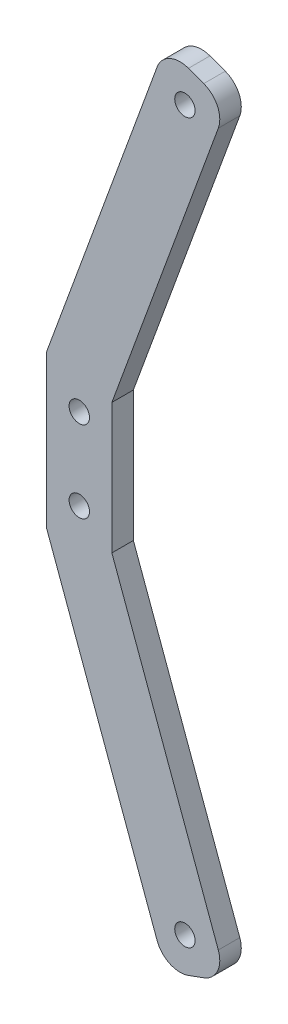
SolidWorks part; units mm, degrees
material "Titanium"
ref_plane "Front Plane" through (0, 0, 0) normal (0, 0, 1) x (1, 0, 0)
ref_plane "Top Plane" through (0, 0, 0) normal (0, 1, 0) x (1, 0, 0)
ref_plane "Right Plane" through (0, 0, 0) normal (1, 0, 0) x (0, 0, -1)
sketch "Sketch1" plane through (0, 0, 0) normal (0, 0, 1) x (1, 0, 0)
  line L0 (0, 0) -> (0, 29.9038)
  line L1 (0, 29.9038) -> (46.3058, 156.3719)
  line L2 (46.3058, 156.3719) -> (70.1572, 147.6388)
  line L3 (70.1572, 147.6388) -> (25.4, 25.4)
  line L4 (25.4, 25.4) -> (25.4, 0)
  line L5 (25.4, 0) -> (0, 0)
  dimension "D1" = 25.4
  dimension "D2" = 20.11
  dimension "D3" = 130.175
  dimension "D4" = 25.4
  dimension "D5" = 25.4
extrude "Extrude1" add sketch "Sketch1" along normal blind 8.382
sketch "Sketch2" plane through (0, 0, 0) normal (0, 0, -1) x (-1, 0, 0)
  line L0 (-25.4, 25.4) -> (-70.1572, 147.6388) construction
  line L1 (-70.1572, 147.6388) -> (-46.3058, 156.3719) construction
  line L2 (0, 29.9038) -> (0, 0) construction
  line L3 (0, 0) -> (-25.4, 0) construction
  circle A0 centre (-53.8649, 140.0796) radius 3.9687
  circle A1 centre (-12.7, 15.875) radius 3.9688
  dimension "D1" = 7.9375
  dimension "D4" = 7.9375
  dimension "D2" = 12.7
  dimension "D3" = 12.7
  dimension "D5" = 12.7
  dimension "D6" = 15.875
extrude "Cut-Extrude1" cut sketch "Sketch2" against normal through all
fillet "Fillet4" radius 9.525 2 edges at (70.1572, 147.6388, 4.191) (46.3058, 156.3719, 4.191)
mirror "Mirror1" about plane through (25.4, 0, 8.382) normal (0, 1, 0) of "Fillet4", "Extrude1", "Cut-Extrude1"
